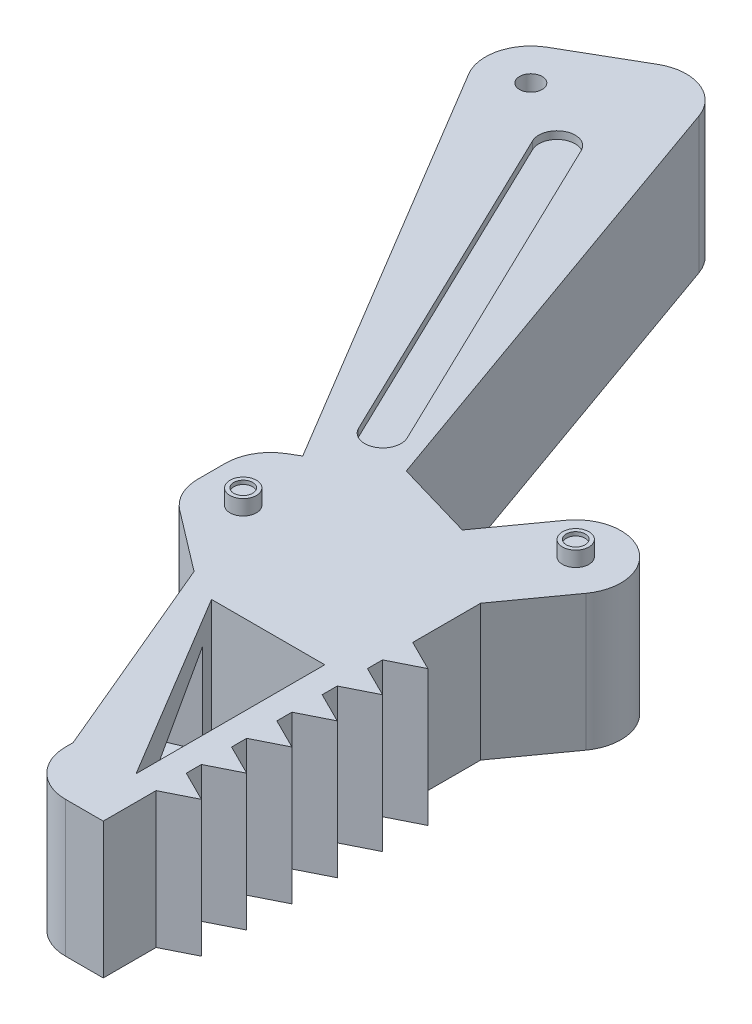
SolidWorks part; units mm, degrees
material "Gray Cast Iron (SN)"
ref_plane "Front" through (0, 0, 0) normal (0, 0, 1) x (1, 0, 0)
ref_plane "Top" through (0, 0, 0) normal (0, 1, 0) x (1, 0, 0)
ref_plane "Right" through (0, 0, 0) normal (1, 0, 0) x (0, 0, -1)
sketch "Sketch1" plane through (0, 0, 0) normal (0, 1, 0) x (1, 0, 0)
  line L0 (2.5141, -21.5751) -> (-33.4558, 38.4763)
  line L1 (-33.4558, 38.4763) -> (-12.6674, 50.4697)
  line L2 (-12.6674, 50.4697) -> (11.0929, -16.4366)
  line L5 (-1.7753, -24.1444) -> (-1.7753, -34.1444)
  line L6 (-1.7753, -34.1444) -> (8.5632, -42.0258)
  line L7 (8.5632, -42.0258) -> (20.1906, -69.6809)
  line L8 (20.1906, -69.6809) -> (20.1906, -76.6809)
  line L9 (20.1906, -76.6809) -> (31.1906, -76.6809)
  line L10 (31.1906, -76.6809) -> (31.1906, -26.6809)
  line L11 (31.1906, -26.6809) -> (37.0304, -18.5632)
  line L12 (11.0929, -16.4366) -> (21.5755, -19.4978)
  line L13 (21.5755, -19.4978) -> (27.2892, -11.5554)
  line L14 (2.5141, -21.5751) -> (-1.7753, -24.1444)
  arc A0 (37.0304, -18.5632) -> (27.2892, -11.5554) centre (32.1598, -15.0593) ccw
  dimension "D1" = 70
  dimension "D2" = 24
  dimension "D3" = 71
  dimension "D4" = 15
  dimension "D5" = 10
  dimension "D6" = 10
  dimension "D7" = 13
  dimension "D8" = 30
  dimension "D9" = 7
  dimension "D10" = 11
  dimension "D11" = 50
  dimension "D12" = 10
  dimension "D13" = 12
extrude "Boss-Extrude1" add sketch "Sketch1" along normal mid plane 18 contours L0 L1 L2 L12 L13 A0 L11 L10 L9 L8 L7 L6 L5 L14
sketch "Sketch2" plane through (0, 9, 0) normal (0, 1, 0) x (1, 0, 0)
  line L0 (12.9281, -44.0713) -> (27.9281, -44.0713)
  line L1 (27.9281, -44.0713) -> (27.9281, -69.0713)
  line L2 (27.9281, -69.0713) -> (12.9281, -44.0713)
  dimension "D1" = 15
  dimension "D2" = 25
extrude "Cut-Extrude1" cut sketch "Sketch2" against normal blind 26
sketch "Sketch3" plane through (0, 9, 0) normal (0, 1, 0) x (1, 0, 0)
  line L0 (31.1906, -76.6809) -> (31.1906, -69.6809)
  line L1 (31.1906, -76.6809) -> (31.1906, -26.6809) construction
  line L2 (31.1906, -69.6809) -> (31.1906, -65.6809)
  line L3 (31.1906, -67.6809) -> (35.1906, -67.6809) construction
  line L4 (31.1906, -65.6809) -> (35.1906, -67.6809)
  line L5 (35.1906, -67.6809) -> (31.1906, -69.6809)
  dimension "D1" = 7
  dimension "D2" = 4
extrude "Boss-Extrude2" add sketch "Sketch3" against normal up to surface (18 mm away) contours L2 L4 L5 up to face at (22.9281, -9, 52.4046)
pattern_linear "LPattern1" count 6 spacing 6 along (0, 0, -1) of "Boss-Extrude2"
fillet "Fillet1" radius 6 2 edges at (-12.6674, 0, -50.4697) (-33.4558, 0, -38.4763)
fillet "Fillet2" radius 6 2 edges at (-1.7753, 0, 24.1444) (-1.7753, 0, 34.1444)
fillet "Fillet3" radius 6 1 edges at (20.1906, 0, 76.6809)
sketch "Sketch4" plane through (0, 9, 0) normal (0, 1, 0) x (1, 0, 0)
  circle A0 centre (-25.1744, 36.3271) radius 1.5
  dimension "D1" = 3
extrude "Cut-Extrude2" cut sketch "Sketch4" against normal through all
sketch "Sketch5" plane through (-7.7384, 0, 3.2535) normal (-0.9218, 0, 0.3876) x (0.3876, 0, 0.9218)
  line L0 (49.0598, 6) -> (49.0598, -6)
  line L1 (42.0598, 9) -> (72.0598, 9) construction
  line L2 (42.0598, -9) -> (72.0598, -9) construction
  line L3 (49.0598, -6) -> (70.0598, -8.2079)
  line L4 (70.0598, -8.2079) -> (70.0598, 3.7921)
  line L5 (70.0598, 3.7921) -> (49.0598, 6)
  line L6 (72.0598, 9) -> (72.0598, -9) construction
  line L7 (42.0598, 9) -> (42.0598, -9) construction
  point P10 (42.0598, 0)
  dimension "D1" = 3
  dimension "D2" = 3
  dimension "D3" = 2
  dimension "D4" = 7
extrude "Cut-Extrude3" cut sketch "Sketch5" against normal blind 9
sketch "Sketch6" plane through (0, 9, 0) normal (0, 1, 0) x (1, 0, 0)
  circle A0 centre (32.1598, -15.0593) radius 1.75
  circle A1 centre (4.2247, -31.1738) radius 1.75
  dimension "D1" = 3.5
extrude "Boss-Extrude3" add sketch "Sketch6" along normal blind 2
sketch "Sketch7" plane through (0, 11, 0) normal (0, 1, 0) x (1, 0, 0)
  circle A2 centre (4.2247, -31.1738) radius 1.25
  circle A3 centre (4.2247, -31.1738) radius 1.25
  circle A5 centre (32.1598, -15.0593) radius 1.25
  circle A6 centre (32.1598, -15.0593) radius 1.25
  dimension "D1" = 0.5
  dimension "D2" = 0.5
extrude "Cut-Extrude4" cut sketch "Sketch7" against normal blind 0.5
sketch "Sketch8" plane through (0, 9, 0) normal (0, 1, 0) x (1, 0, 0)
  line L0 (-16.258, 30.8765) -> (5.194, -13.6421) construction
  line L1 (-14.087, 31.9226) -> (7.365, -12.596)
  line L2 (-18.429, 29.8304) -> (3.023, -14.6883)
  arc A0 (-14.087, 31.9226) -> (-18.429, 29.8304) centre (-16.258, 30.8765) ccw
  arc A1 (3.023, -14.6883) -> (7.365, -12.596) centre (5.194, -13.6421) ccw
  point P2 (-5.532, 8.6172)
extrude "Cut-Extrude5" cut sketch "Sketch8" against normal blind 1
mirror "Mirror1" about plane through (0, 0, 0) normal (0, 1, 0) of "Cut-Extrude5", "Cut-Extrude4", "Boss-Extrude3"
